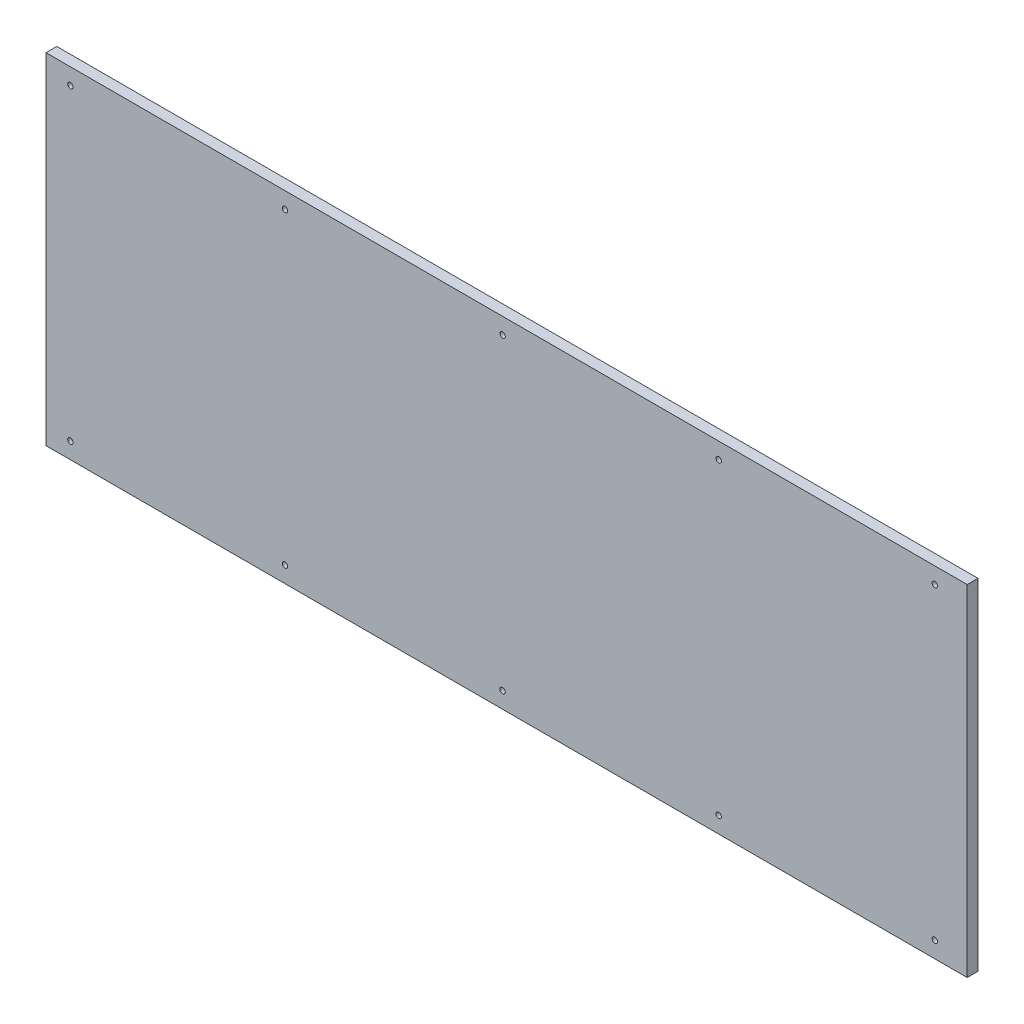
SolidWorks part; units mm, degrees
ref_plane "Front" through (0, 0, 0) normal (0, 0, 1) x (1, 0, 0)
ref_plane "Top" through (0, 0, 0) normal (0, 1, 0) x (1, 0, 0)
ref_plane "Right" through (0, 0, 0) normal (1, 0, 0) x (0, 0, -1)
sketch "Sketch1" plane through (0, 0, 0) normal (0, 0, 1) x (1, 0, 0)
  line L1 (0, 0) -> (-1082.802, 0)
  line L2 (0, 0) -> (0, 400.05)
  line L3 (0, 400.05) -> (-1082.802, 400.05)
  line L4 (-1082.802, 0) -> (-1082.802, 400.05)
  dimension "D1" = 1082.802
  dimension "D2" = 400.05
extrude "Boss-Extrude1" add sketch "Sketch1" along normal blind 12.7
sketch "Sketch2"
  line L2 (-1082.802, 0) -> (0, 0) construction
  line L3 (-1082.802, 400.05) -> (-1082.802, 0) construction
  line L4 (-1082.802, 200.025) -> (0, 200.025) construction
  line L5 (0, 0) -> (0, 400.05) construction
  circle A1 centre (-1054.1, 19.05) radius 3.175
  circle A2 centre (-801.878, 19.05) radius 3.175
  circle A3 centre (-546.1, 19.05) radius 3.175
  circle A4 centre (-292.1, 19.05) radius 3.175
  circle A5 centre (-38.1, 19.05) radius 3.175
  circle A6 centre (-38.1, 381) radius 3.175
  circle A7 centre (-292.1, 381) radius 3.175
  circle A8 centre (-546.1, 381) radius 3.175
  circle A9 centre (-801.878, 381) radius 3.175
  circle A10 centre (-1054.1, 381) radius 3.175
  point P16 (-1082.802, 200.025)
  point P17 (0, 200.025)
other "AlignGroup1" parameters "D2"=45.4031, "D3"=28.702, "D9"=6.35, "D1"=325.1078, "D4"=36.3801, "D5"=381, "D6"=0, "D7"=280.924, "D8"=536.702, "D10"=381
other "AlignGroup2"
other "AlignGroup3"
extrude "Cut-Extrude1" cut sketch "Sketch2" against normal through all
